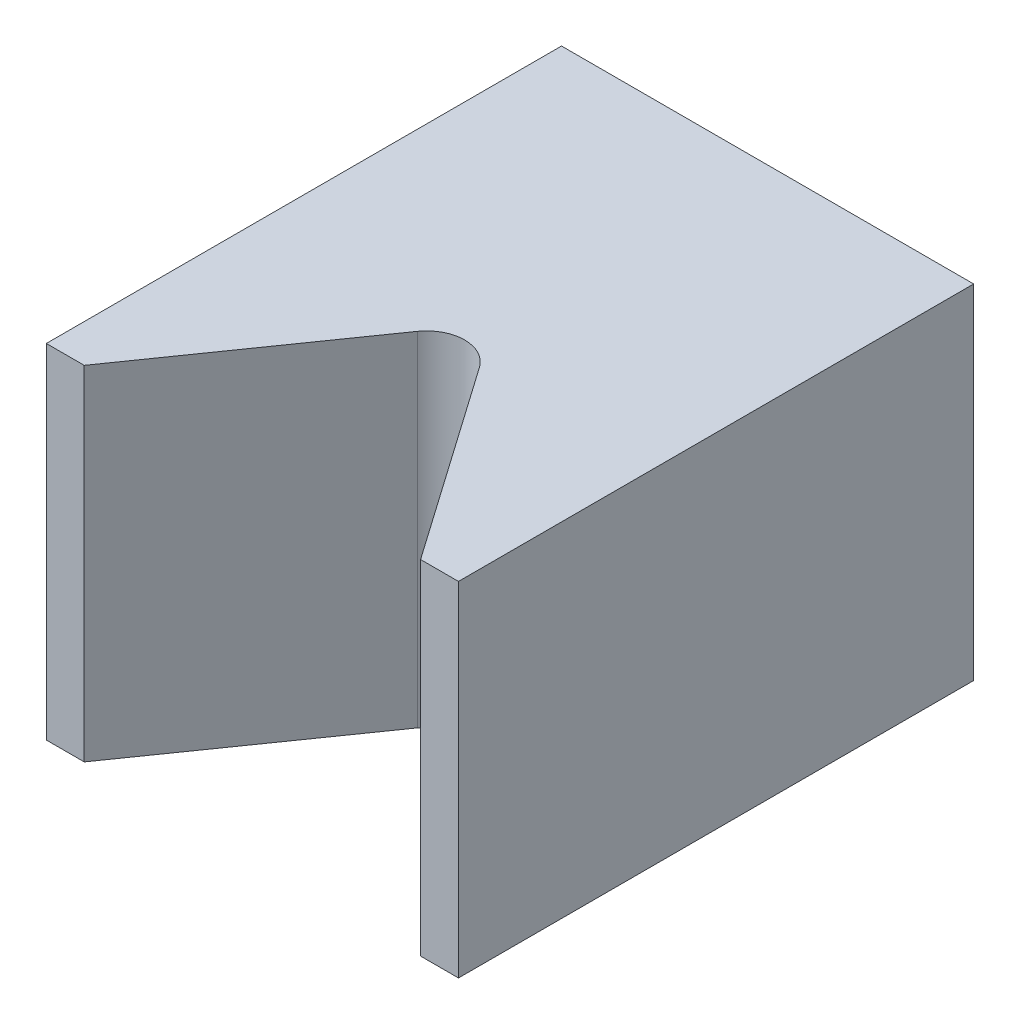
SolidWorks part; units mm, degrees
ref_plane "Front Plane" through (0, 0, 0) normal (0, 0, 1) x (1, 0, 0)
ref_plane "Top Plane" through (0, 0, 0) normal (0, 1, 0) x (1, 0, 0)
ref_plane "Right Plane" through (0, 0, 0) normal (1, 0, 0) x (0, 0, -1)
sketch "Sketch1" plane through (0, 0, 0) normal (0, 1, 0) x (1, 0, 0)
  line L0 (0.9046, 0.6327) -> (4.896, -5.0739)
  line L1 (4.896, -5.0739) -> (6, -5.0739)
  line L2 (6, -5.0739) -> (6, 9.9261)
  line L3 (6, 9.9261) -> (-6, 9.9261)
  line L4 (-6, 9.9261) -> (-6, -5.0739)
  line L5 (-6, -5.0739) -> (-4.896, -5.0739)
  line L6 (-4.896, -5.0739) -> (-0.9046, 0.6327)
  arc A0 (0.9046, 0.6327) -> (-0.9046, 0.6327) centre (0, 0) ccw
  dimension "D4" = 1.104
  dimension "D1" = 15
  dimension "D3" = 12
  dimension "D5" = 6.9639
  dimension "D6" = 6.9639
  dimension "D7" = 1.104
  dimension "D8" = 1.104
  dimension "D9" = 1.8093
  dimension "D10" = 55.03
extrude "Boss-Extrude1" add sketch "Sketch1" along normal blind 10
sketch "Sketch2" plane through (0, 0, -9.9261) normal (0, 0, -1) x (-1, 0, 0)
  line L0 (0, 0) -> (0, 10)
  line L1 (-6, 10) -> (6, 10) construction
  circle A0 centre (0, 5) radius 2.1
  dimension "D1" = 4.2
extrude "Cut-Extrude1" cut sketch "Sketch2" against normal blind 7 contours L0 A0 | L0 A0
